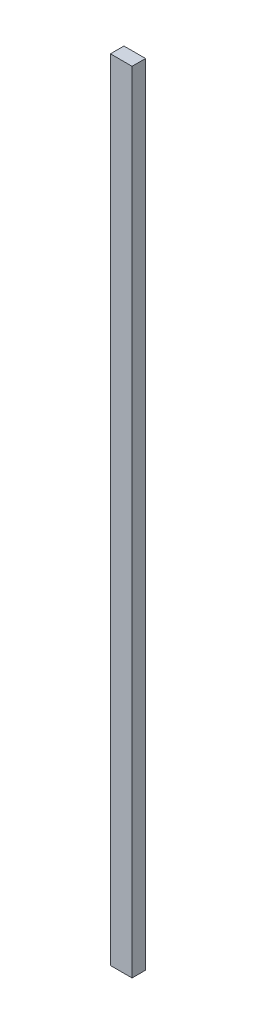
SolidWorks part; units mm, degrees
ref_plane "Front Plane" through (0, 0, 0) normal (0, 0, 1) x (1, 0, 0)
ref_plane "Top Plane" through (0, 0, 0) normal (0, 1, 0) x (1, 0, 0)
ref_plane "Right Plane" through (0, 0, 0) normal (1, 0, 0) x (0, 0, -1)
other "Configuration Table"
sketch "Sketch1" plane through (0, 0, 0) normal (0, 0, 1) x (1, 0, 0)
  line L1 (1290, 200) -> (1330, 200)
  line L2 (1290, 200) -> (1290, 1660)
  line L3 (1290, 1660) -> (1330, 1660)
  line L4 (1330, 200) -> (1330, 1660)
extrude "STORE_kablo_kanali_dikey_40x25_1" add sketch "Sketch1" against normal blind 25 from offset 727 separate body
